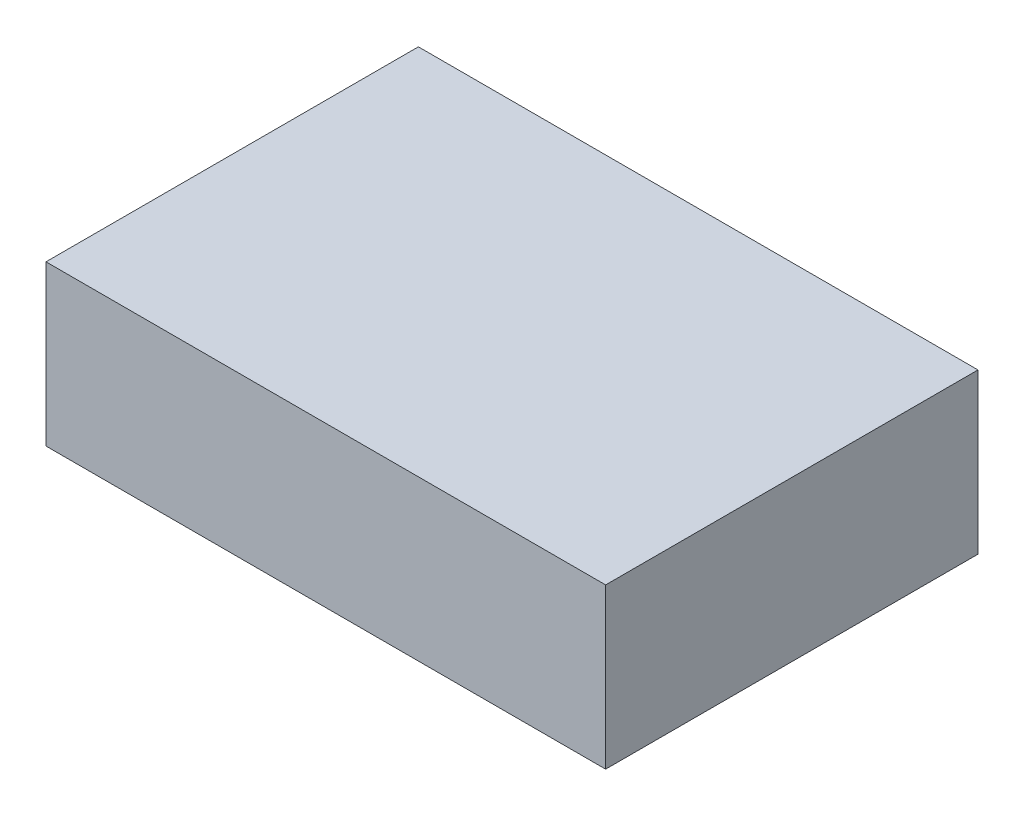
SolidWorks part; units mm, degrees
ref_plane "Front Plane" through (0, 0, 0) normal (0, 0, 1) x (1, 0, 0)
ref_plane "Top Plane" through (0, 0, 0) normal (0, 1, 0) x (1, 0, 0)
ref_plane "Right Plane" through (0, 0, 0) normal (1, 0, 0) x (0, 0, -1)
sketch "Sketch1" plane through (0, 0, 0) normal (0, 1, 0) x (1, 0, 0)
  line L1 (-26.3, 17.5) -> (26.3, 17.5)
  line L2 (-26.3, 17.5) -> (-26.3, -17.5)
  line L3 (-26.3, -17.5) -> (26.3, -17.5)
  line L4 (26.3, 17.5) -> (26.3, -17.5)
  line L5 (-26.3, 17.5) -> (26.3, -17.5) construction
  line L6 (-26.3, -17.5) -> (26.3, 17.5) construction
  point P0 (0, 0)
  dimension "D1" = 52.6
  dimension "D2" = 35
extrude "Boss-Extrude1" add sketch "Sketch1" along normal blind 15
sketch "Sketch2" plane through (0, 15, 0) normal (0, 1, 0) x (1, 0, 0)
  line L0 (0, -17.5) -> (0, 17.5) construction
  line L1 (-26.3, -17.5) -> (26.3, -17.5) construction
  line L2 (26.3, 17.5) -> (-26.3, 17.5) construction
  line L3 (-26.3, 0) -> (26.3, 0) construction
  line L4 (-26.3, 17.5) -> (-26.3, -17.5) construction
  line L5 (26.3, -17.5) -> (26.3, 17.5) construction
  line L6 (-26.3, -7.55) -> (26.3, -7.55) construction
  line L7 (-26.3, 7.55) -> (26.3, 7.55) construction
  dimension "D1" = 7.55
  dimension "D2" = 7.55
